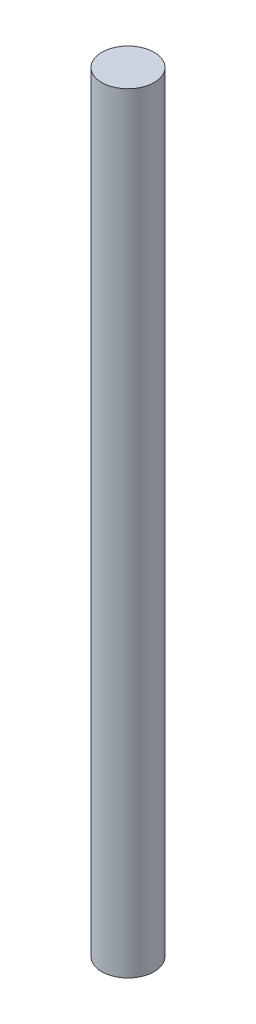
SolidWorks part; units mm, degrees
ref_plane "Front Plane" through (0, 0, 0) normal (0, 0, 1) x (1, 0, 0)
ref_plane "Top Plane" through (0, 0, 0) normal (0, 1, 0) x (1, 0, 0)
ref_plane "Right Plane" through (0, 0, 0) normal (1, 0, 0) x (0, 0, -1)
sketch "Sketch1" plane through (0, 0, 0) normal (0, 1, 0) x (1, 0, 0)
  circle A0 centre (0, 0) radius 4.7625
extrude "Boss-Extrude1" add sketch "Sketch1" along normal blind 140
sketch "Sketch9" plane through (0, 0, 0) normal (0, -1, 0) x (1, 0, 0)
  circle A0 centre (0, 0) radius 1.55
extrude "Cut-Extrude1" cut sketch "Sketch9" against normal blind 9.2
